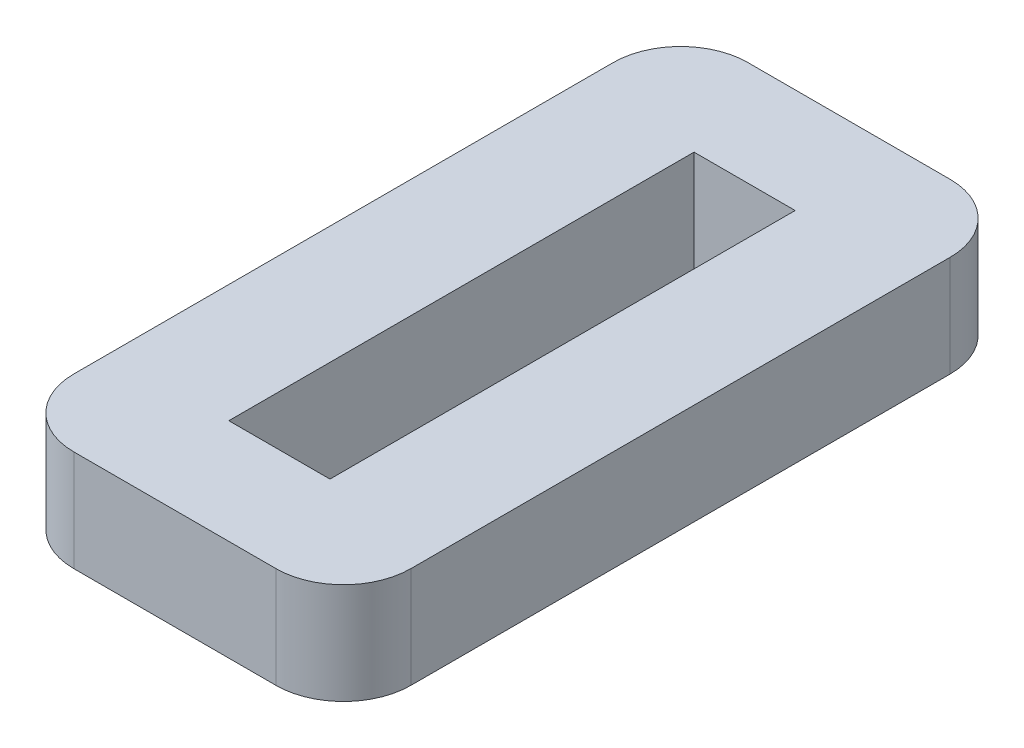
SolidWorks part; units mm, degrees
ref_plane "Спереди" through (0, 0, 0) normal (0, 0, 1) x (1, 0, 0)
ref_plane "Сверху" through (0, 0, 0) normal (0, 1, 0) x (1, 0, 0)
ref_plane "Справа" through (0, 0, 0) normal (1, 0, 0) x (0, 0, -1)
other "Configuration Table"
sketch "Эскиз1" plane through (0, 0, 0) normal (0, 1, 0) x (1, 0, 0)
  line L1 (-5, -10) -> (5, -10)
  line L2 (-5, -10) -> (-5, 10)
  line L3 (-5, 10) -> (5, 10)
  line L4 (5, -10) -> (5, 10)
  line L5 (-5, -10) -> (5, 10) construction
  line L6 (-5, 10) -> (5, -10) construction
  point P0 (0, 0)
  dimension "D1" = 20
  dimension "D2" = 10
extrude "Бобышка-Вытянуть1" add sketch "Эскиз1" along normal blind 3
sketch "Эскиз2" plane through (0, 3, 0) normal (0, 1, 0) x (1, 0, 0)
  line L1 (-1.5, -6.9) -> (1.5, -6.9)
  line L2 (-1.5, -6.9) -> (-1.5, 6.9)
  line L3 (-1.5, 6.9) -> (1.5, 6.9)
  line L4 (1.5, -6.9) -> (1.5, 6.9)
  line L5 (-1.5, -6.9) -> (1.5, 6.9) construction
  line L6 (-1.5, 6.9) -> (1.5, -6.9) construction
  point P0 (0, 0)
  dimension "D1" = 3
  dimension "D2" = 13.8
extrude "Вырез-Вытянуть1" cut sketch "Эскиз2" against normal blind 3
fillet "Скругление1" radius 2 4 edges at (-5, 1.5, 10) (5, 1.5, 10) (5, 1.5, -10) (-5, 1.5, -10)
sketch "Эскиз4" plane through (0, 3, 0) normal (0, 1, 0) x (1, 0, 0)
  line L0 (1.5, 6.9) -> (-1.5, 6.9) construction
  line L1 (1.5, -6.9) -> (1.5, 6.9) construction
  line L2 (-1.5, -6.9) -> (1.5, -6.9) construction
  line L3 (-1.5, 6.9) -> (-1.5, -6.9) construction
  line L4 (-5, 8) -> (-5, -8)
  line L5 (-3, -10) -> (3, -10)
  line L6 (5, -8) -> (5, 8)
  line L7 (3, 10) -> (-3, 10)
  line L8 (-5, 8) -> (-5, -8)
  line L9 (-3, -10) -> (3, -10)
  line L10 (5, -8) -> (5, 8)
  line L11 (3, 10) -> (-3, 10)
  line L12 (1.5, 6.9) -> (-1.5, 6.9)
  line L13 (1.5, -6.9) -> (1.5, 6.9)
  line L14 (-1.5, -6.9) -> (1.5, -6.9)
  line L15 (-1.5, 6.9) -> (-1.5, -6.9)
  arc A4 (-5, -8) -> (-3, -10) centre (-3, -8) ccw
  arc A5 (3, -10) -> (5, -8) centre (3, -8) ccw
  arc A6 (5, 8) -> (3, 10) centre (3, 8) ccw
  arc A7 (-3, 10) -> (-5, 8) centre (-3, 8) ccw
  arc A8 (-5, -8) -> (-3, -10) centre (-3, -8) ccw
  arc A9 (3, -10) -> (5, -8) centre (3, -8) ccw
  arc A10 (5, 8) -> (3, 10) centre (3, 8) ccw
  arc A11 (-3, 10) -> (-5, 8) centre (-3, 8) ccw
  dimension "D1" = 0
